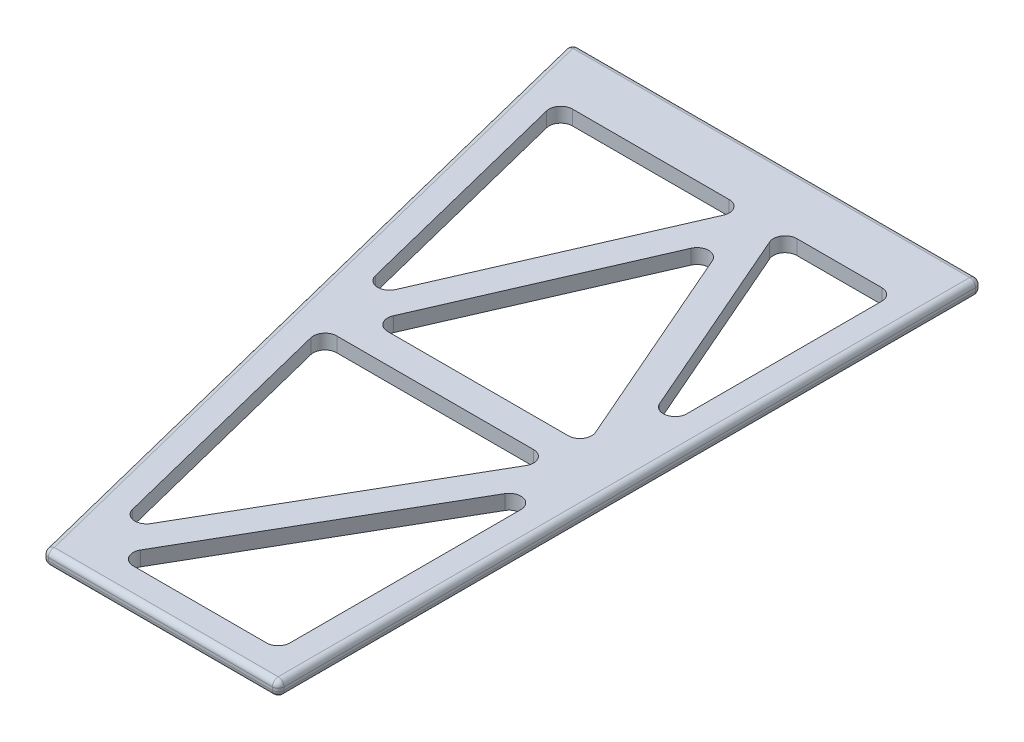
SolidWorks part; units mm, degrees
other "Markup1"
sketch "Sketch6" plane through (-76.2, 0, 0) normal (0.4646, -0.8816, -0.0837) x (0.8814, 0.4695, -0.0527)
material "Teak"
ref_plane "Front" through (0, 0, 0) normal (0, 0, 1) x (1, 0, 0)
ref_plane "Top" through (0, 0, 0) normal (0, 1, 0) x (1, 0, 0)
ref_plane "Right" through (0, 0, 0) normal (1, 0, 0) x (0, 0, -1)
sketch "Sketch1" plane through (0, 0, 0) normal (0, 0, 1) x (1, 0, 0)
  line L1 (0, 0) -> (-254, 0)
  line L2 (0, 0) -> (0, 6.35)
  line L3 (0, 6.35) -> (-254, 6.35)
  line L4 (-254, 0) -> (-254, 6.35)
  dimension "D1" = 6.35
  dimension "D2" = 254
extrude "Boss-Extrude1" add sketch "Sketch1" along normal blind 304.8 contours L3 L4 L1 L2
sketch "Sketch2" plane through (0, 6.35, 0) normal (0, 1, 0) x (1, 0, 0)
  line L0 (-254, 0) -> (-177.8, -304.8)
  line L1 (0, -304.8) -> (-254, -304.8) construction
  line L2 (0, -304.8) -> (-254, -304.8)
  line L3 (0, -304.8) -> (-254, -304.8)
  line L4 (-254, -304.8) -> (-254, 0)
  line L5 (-254, -304.8) -> (-254, 0)
  line L6 (-254, 0) -> (0, 0)
  line L7 (-254, 0) -> (0, 0)
  line L8 (0, 0) -> (0, -304.8)
  line L9 (0, 0) -> (0, -304.8)
  line M2 (-254, 0) -> (-254, -304.8)
  line M3 (-254, -304.8) -> (0, -304.8)
  dimension "D1" = 177.8
extrude "Cut-Extrude1" cut sketch "Sketch2" against normal blind 304.8 contours L0 M2 M3
sketch "Sketch4" plane through (0, 6.35, 0) normal (0, 1, 0) x (1, 0, 0)
  line L0 (0, -304.8) -> (-177.8, -304.8) construction
  line L1 (-76.2, 0) -> (-257.808, 0)
  line L5 (-76.2, -127) -> (-76.2, 0)
  line L7 (-76.2, -304.8) -> (-76.2, -177.8)
  line L8 (-76.2, 0) -> (29.5686, 0)
  line L11 (0, 0) -> (-254, 0) construction
  line L12 (-76.2, -177.8) -> (-76.2, -304.8)
  line L17 (-76.2, -304.8) -> (0, -304.8)
  line L18 (0, -304.8) -> (0, 0)
  line L19 (0, 0) -> (-76.2, 0)
  line L26 (-76.2, -177.8) -> (-76.2, -127)
  point P5 (0, -152.4)
  dimension "D1" = 76.2
  dimension "D2" = 25.4
  dimension "D5" = 76.2
extrude "Cut-Extrude2" cut sketch "Sketch4" against normal through all
sketch "Sketch7" plane through (0, 0, 0) normal (0, -1, 0) x (-1, 0, 0)
  line L0 (165.1, 0) -> (165.1, -25.4)
  line L1 (76.2, 0) -> (254, 0) construction
  line L2 (-887.9677, -25.4) -> (138.5661, -25.4) construction
  line L4 (167.8841, -292.1) -> (-92.3416, -1333.0029) construction
  line L5 (76.2, -304.8) -> (76.2, 0) construction
  line L6 (88.9, -1152.4) -> (88.9, -167.9955) construction
  line L7 (127, -304.8) -> (127, -292.1)
  line L8 (76.2, -304.8) -> (177.8, -304.8) construction
  line L9 (127, -292.1) -> (160.5518, -292.1) construction
  line L10 (152.4191, -25.4) -> (247.65, -25.4) construction
  line L11 (167.8841, -292.1) -> (1170.6683, -292.1) construction
  line L12 (446.1148, 820.8227) -> (204.6107, -145.1938) construction
  line L13 (88.9, -139.3973) -> (88.9, -104.9285) construction
  line L16 (163.8188, -272.3585) -> (104.2979, -169.2655)
  line L17 (156.1524, -284.48) -> (98.3794, -184.4143)
  line L19 (198.6467, -131.5048) -> (155.5164, -32.509)
  line L20 (135.4689, -32.509) -> (98.6372, -117.0478)
  line L21 (106.3475, -148.9455) -> (184.6378, -148.9455)
  line L22 (189.295, -141.8364) -> (150.1498, -51.9877)
  line L23 (140.8354, -51.9877) -> (101.6903, -141.8364)
  line L24 (173.1465, -271.0506) -> (198.9198, -167.9575)
  line L25 (228.0528, -25.4) -> (160.1736, -25.4)
  line L26 (88.9, -30.48) -> (88.9, -115.0187)
  line L27 (93.98, -292.1) -> (151.753, -292.1)
  line L28 (88.9, -186.9543) -> (88.9, -287.02)
  line L29 (200.4978, -161.6455) -> (170.0998, -283.2376) construction
  line L30 (208.2322, -130.7078) -> (232.9811, -31.7121)
  line L31 (130.8117, -25.4) -> (93.98, -25.4)
  line L32 (108.6973, -161.6455) -> (193.9914, -161.6455)
  arc A0 (184.6378, -148.9455) -> (189.295, -141.8364) centre (184.6378, -143.8655) ccw
  arc A1 (106.3475, -148.9455) -> (101.6903, -141.8364) centre (106.3475, -143.8655) cw
  arc A2 (150.1498, -51.9877) -> (140.8354, -51.9877) centre (145.4926, -54.0167) ccw
  arc A3 (93.98, -25.4) -> (88.9, -30.48) centre (93.98, -30.48) ccw
  arc A4 (135.4689, -32.509) -> (130.8117, -25.4) centre (130.8117, -30.48) ccw
  arc A5 (155.5164, -32.509) -> (160.1736, -25.4) centre (160.1736, -30.48) cw
  arc A6 (232.9811, -31.7121) -> (228.0528, -25.4) centre (228.0528, -30.48) ccw
  arc A7 (198.6467, -131.5048) -> (208.2322, -130.7078) centre (203.3039, -129.4757) ccw
  arc A8 (98.6372, -117.0478) -> (88.9, -115.0187) centre (93.98, -115.0187) cw
  arc A9 (98.3794, -184.4143) -> (88.9, -186.9543) centre (93.98, -186.9543) ccw
  arc A10 (88.9, -287.02) -> (93.98, -292.1) centre (93.98, -287.02) ccw
  arc A11 (156.1524, -284.48) -> (151.753, -292.1) centre (151.753, -287.02) cw
  arc A12 (163.8188, -272.3585) -> (173.1465, -271.0506) centre (168.2182, -269.8185) ccw
  arc A13 (198.9198, -167.9575) -> (193.9914, -161.6455) centre (193.9914, -166.7255) ccw
  arc A14 (104.2979, -169.2655) -> (108.6973, -161.6455) centre (108.6973, -166.7255) cw
  point P30 (88.9, -25.4)
  point P50 (234.5591, -25.4)
  point P63 (88.9, -292.1)
  dimension "D4" = 5.08
  dimension "D1" = 12.7
  dimension "D2" = 12.7
  dimension "D3" = 25.4
extrude "Cut-Extrude3" cut sketch "Sketch7" against normal up to next contours A8 L20 A4 L31 A3 L26 | L19 A7 L30 A6 L25 A5 | A11 L17 A9 L28 A10 L27 | L24 A13 L32 A14 L16 A12 | A1 L23 A2 L22 A0 L21
fillet "Fillet2" radius 2.54 12 edges at (-127, 6.35, 304.8) (-127, 0, 304.8) (-177.8, 3.175, 304.8) (-215.9, 6.35, 152.4) (-215.9, 0, 152.4) (-165.1, 6.35, 0) (-165.1, 0, 0) (-254, 3.175, 0) (-76.2, 3.175, 304.8) (-76.2, 0, 152.4) (-76.2, 6.35, 152.4) (-76.2, 3.175, 0)
